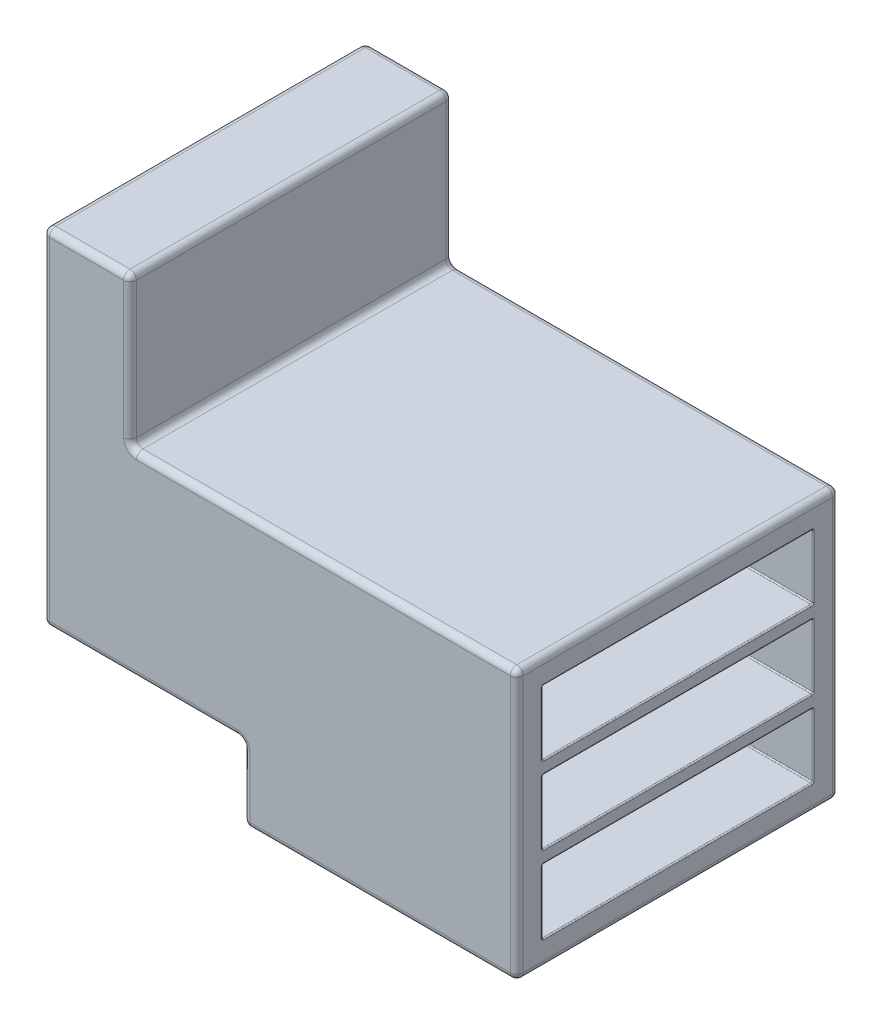
SolidWorks part; units mm, degrees
ref_plane "Front Plane" through (0, 0, 0) normal (0, 0, 1) x (1, 0, 0)
ref_plane "Top Plane" through (0, 0, 0) normal (0, 1, 0) x (1, 0, 0)
ref_plane "Right Plane" through (0, 0, 0) normal (1, 0, 0) x (0, 0, -1)
sketch "Sketch1" plane through (0, 0, 0) normal (0, 1, 0) x (1, 0, 0)
  line L1 (0, 0) -> (735, 0)
  line L2 (0, 0) -> (0, 500)
  line L3 (0, 500) -> (735, 500)
  line L4 (735, 0) -> (735, 500)
  dimension "D1" = 735
  dimension "D2" = 500
extrude "Boss-Extrude1" add sketch "Sketch1" along normal blind 418.8
sketch "Sketch6" plane through (0, 0, 0) normal (-1, 0, 0) x (0, 0, 1)
  line L0 (-500, 418.8) -> (-500, 0) construction
  line L1 (0, 418.8) -> (-500, 418.8)
  line L2 (0, 418.8) -> (0, 650.4)
  line L3 (0, 650.4) -> (-500, 650.4)
  line L4 (-500, 418.8) -> (-500, 650.4)
  line L5 (-500, 0) -> (0, 0) construction
  dimension "D1" = 650.4
extrude "Boss-Extrude2" add sketch "Sketch6" against normal blind 135
sketch "Sketch2" plane through (0, 0, 0) normal (0, 0, 1) x (1, 0, 0)
  line L1 (0, 0) -> (311, 0)
  line L2 (0, 0) -> (0, 115)
  line L3 (0, 115) -> (311, 115)
  line L4 (311, 0) -> (311, 115)
  dimension "D1" = 311
  dimension "D2" = 115
extrude "Cut-Extrude1" cut sketch "Sketch2" against normal up to surface (500 mm away) up to face at (290, 356.4, -500)
fillet "Fillet1" radius 10 24 edges at (523, 0, -500) (311, 0, -250) (311, 57.5, -500) (311, 115, -250) (155.5, 115, -500) (0, 115, -250) (0, 382.7, -500) (435, 418.8, -500) (435, 418.8, 0) (523, 0, 0) (311, 57.5, 0) (155.5, 115, 0) (0, 382.7, 0) (735, 209.4, 0) (735, 418.8, -250) (735, 209.4, -500) (735, 0, -250) (135, 534.6, -500) (67.5, 650.4, -500) (0, 650.4, -250) (135, 650.4, -250) (135, 418.8, -250) (67.5, 650.4, 0) (135, 534.6, 0)
sketch "Sketch4" plane through (735, 0, 0) normal (1, 0, 0) x (0, 0, -1)
  line L0 (490, 0) -> (10, 0) construction
  line L1 (40, 40) -> (460, 40)
  line L2 (40, 40) -> (40, 140)
  line L3 (40, 140) -> (460, 140)
  line L4 (460, 40) -> (460, 140)
  line L5 (0, 10) -> (0, 408.8) construction
  line L6 (500, 408.8) -> (500, 10) construction
  dimension "D1" = 40
  dimension "D2" = 40
  dimension "D3" = 40
  dimension "D4" = 100
extrude "Cut-Extrude2" cut sketch "Sketch4" against normal blind 170
sketch "Sketch5" plane through (735, 0, 0) normal (1, 0, 0) x (0, 0, -1)
  line L0 (40, 140) -> (40, 40) construction
  line L1 (40, 160) -> (460, 160)
  line L2 (40, 160) -> (40, 260)
  line L3 (40, 260) -> (460, 260)
  line L4 (460, 160) -> (460, 260)
  line L5 (40, 280) -> (460, 280)
  line L6 (40, 280) -> (40, 380)
  line L7 (40, 380) -> (460, 380)
  line L8 (460, 280) -> (460, 380)
  line L9 (40, 140) -> (40, 40) construction
  line L10 (460, 40) -> (460, 140) construction
  line L11 (460, 40) -> (460, 140) construction
  line L12 (460, 140) -> (40, 140) construction
  dimension "D1" = 100
  dimension "D2" = 100
  dimension "D3" = 20
  dimension "D4" = 20
extrude "Cut-Extrude3" cut sketch "Sketch5" against normal blind 470
fillet "Fillet2" radius 2 36 edges at (265, 260, -250) (735, 260, -250) (735, 330, -460) (500, 280, -460) (735, 280, -250) (500, 380, -460) (735, 380, -250) (500, 380, -40) (500, 280, -40) (735, 330, -40) (265, 380, -250) (265, 330, -460) (265, 280, -250) (265, 330, -40) (500, 260, -40) (265, 210, -40) (735, 210, -40) (265, 210, -460) (500, 260, -460) (735, 210, -460) (500, 160, -40) (265, 160, -250) (500, 160, -460) (735, 160, -250) (735, 90, -40) (650, 40, -40) (735, 40, -250) (650, 40, -460) (735, 90, -460) (650, 140, -460) (650, 140, -40) (735, 140, -250) (565, 140, -250) (565, 90, -460) (565, 40, -250) (565, 90, -40)
